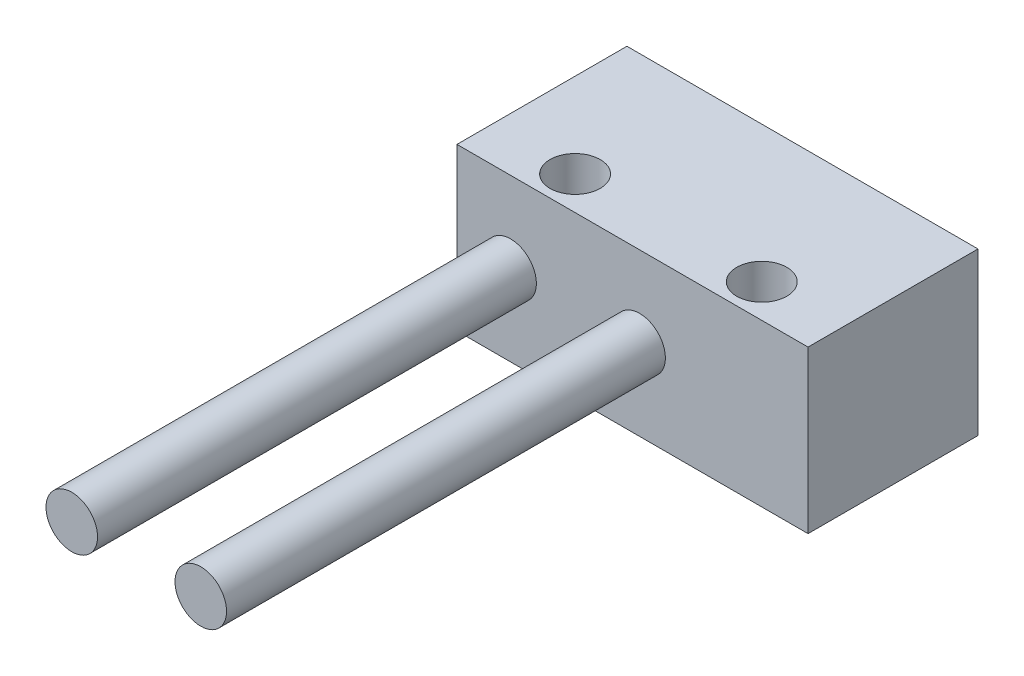
SolidWorks part; units mm, degrees
ref_plane "Front Plane" through (0, 0, 0) normal (0, 0, 1) x (1, 0, 0)
ref_plane "Top Plane" through (0, 0, 0) normal (0, 1, 0) x (1, 0, 0)
ref_plane "Right Plane" through (0, 0, 0) normal (1, 0, 0) x (0, 0, -1)
sketch "Sketch1" plane through (0, 0, 0) normal (0, 1, 0) x (1, 0, 0)
  line L0 (2.14, 1.2) -> (3.04, 1.2) construction
  line L1 (0, 0) -> (12.6, 0)
  line L2 (0, 0) -> (0, 6.1)
  line L3 (0, 6.1) -> (12.6, 6.1)
  line L4 (12.6, 0) -> (12.6, 6.1)
  line L5 (3.04, 1.2) -> (3.04, 2.1) construction
  circle A0 centre (3.04, 1.2) radius 0.9
  circle A1 centre (9.74, 1.2) radius 0.9
  dimension "D3" = 1.8
  dimension "D1" = 12.6
  dimension "D2" = 6.1
  dimension "D4" = 6.7
  dimension "D5" = 2.14
  dimension "D6" = 4
extrude "Boss-Extrude1" add sketch "Sketch1" along normal blind 5.8
sketch "Sketch2" plane through (0, 0, -6.1) normal (0, 0, -1) x (-1, 0, 0)
  line L0 (0, 2.9) -> (-1.0138, 2.9) construction
  line L1 (-5, 1.525) -> (-4, 1.525)
  line L2 (-5, 1.525) -> (-5, 4.275)
  line L3 (-5, 4.275) -> (-4, 4.275)
  line L4 (-4, 1.525) -> (-4, 4.275)
  line L5 (0, 5.8) -> (0, 0) construction
  point P9 (-4, 2.9)
  dimension "D1" = 2.75
  dimension "D2" = 4
  dimension "D3" = 1
extrude "Boss-Extrude2" add sketch "Sketch2" along normal blind 1
sketch "Sketch3" plane through (0, 0, 0) normal (0, 0, 1) x (1, 0, 0)
  line L0 (12.6, 2.9) -> (8.7024, 2.9) construction
  line L1 (12.6, 5.8) -> (12.6, 0) construction
  line L2 (1.925, 2.9) -> (2.85, 2.9) construction
  line L3 (0, 5.8) -> (0, 0) construction
  circle A0 centre (1.925, 2.9) radius 0.925
  circle A1 centre (6.555, 2.9) radius 0.925
  dimension "D1" = 1.85
  dimension "D2" = 4.63
  dimension "D3" = 2.85
extrude "Boss-Extrude3" add sketch "Sketch3" along normal blind 15.75
